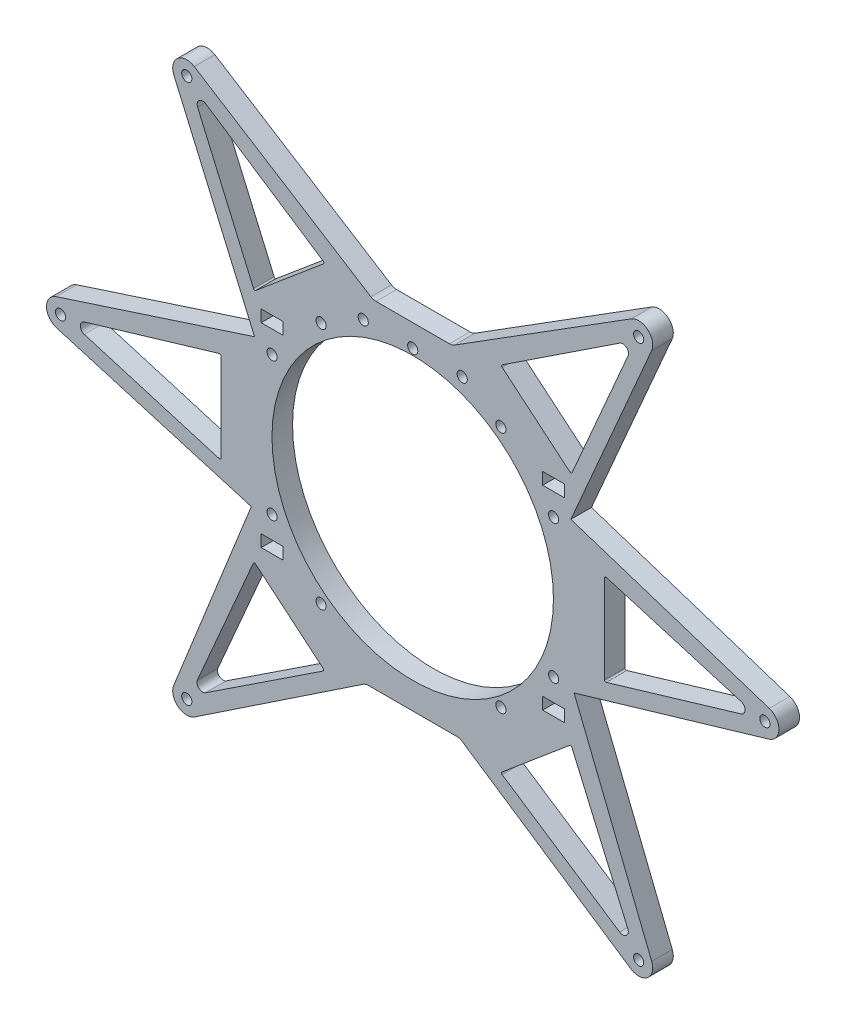
SolidWorks part; units mm, degrees
ref_plane "Front Plane" through (0, 0, 0) normal (0, 0, 1) x (1, 0, 0)
ref_plane "Top Plane" through (0, 0, 0) normal (0, 1, 0) x (1, 0, 0)
ref_plane "Right Plane" through (0, 0, 0) normal (1, 0, 0) x (0, 0, -1)
sketch "Sketch1" plane through (0, 0, 0) normal (0, 0, 1) x (1, 0, 0)
  line L0 (595.6845, 438.9915) -> (595.6626, 464.0842)
  line L1 (548.8362, 455.2938) -> (605.2132, 473.6179)
  line L2 (607.0986, 422.6607) -> (613.2986, 426.0607) construction
  line L3 (610.1986, 424.3607) -> (610.1986, 432.3607) construction
  line L4 (610.1986, 432.3607) -> (610.1986, 424.3607) construction
  line L5 (607.0986, 426.0607) -> (613.2986, 422.6607) construction
  line L6 (556.8144, 453.0549) -> (595.1528, 464.464)
  line L7 (556.8142, 450.0066) -> (595.1515, 438.5937)
  line L8 (548.9419, 447.6528) -> (604.2858, 431.3431)
  line L9 (624.7181, 401.7252) -> (605.4819, 417.8376)
  line L10 (607.0986, 426.0607) -> (607.0986, 422.6607)
  line L11 (607.0986, 426.0607) -> (613.2986, 426.0607)
  line L12 (613.2986, 426.0607) -> (613.2986, 422.6607)
  line L13 (588.9596, 380.9888) -> (604.8633, 417.6913)
  line L14 (588.0779, 531.5374) -> (638.2665, 499.9901)
  line L15 (591.2947, 379.0292) -> (624.6802, 401.0612)
  line L16 (607.0986, 422.6607) -> (613.2986, 422.6607)
  line L17 (709.0257, 523.9501) -> (675.6402, 501.9182)
  line L18 (639.7249, 499.5698) -> (660.5955, 499.5698)
  line L19 (589.0225, 522.0435) -> (604.9224, 485.3394)
  line L20 (637.6128, 403.9671) -> (641.8406, 403.9671)
  line L21 (690.1986, 470.2607) -> (690.1986, 433.8107) construction
  line L22 (693.2986, 481.4107) -> (687.0986, 478.0107) construction
  line L23 (690.1986, 479.7107) -> (690.1986, 471.7107) construction
  line L24 (582.2362, 376.3163) -> (604.2858, 431.3431)
  line L25 (675.6023, 501.2542) -> (694.8386, 485.1417)
  line L26 (582.2787, 526.5609) -> (605.2132, 473.6179)
  line L27 (690.1986, 471.7107) -> (690.1986, 479.7107) construction
  line L28 (712.2426, 531.5374) -> (662.0539, 499.9901)
  line L29 (650.0692, 451.5983) -> (-31455.4559, 38782.203) construction
  line L30 (605.5697, 485.1868) -> (624.7777, 501.3329)
  line L31 (591.3577, 524.0028) -> (624.741, 501.9675)
  line L32 (625.1052, 486.4638) -> (676.2052, 486.4388) construction
  line L33 (676.2052, 486.4388) -> (676.2052, 417.3888) construction
  line L34 (650.5503, 451.9554) -> (-31454.9748, -37878.6493) construction
  line L35 (588.1707, 371.5021) -> (636.1508, 403.5468)
  line L36 (711.3608, 521.9906) -> (695.4572, 485.2881)
  line L37 (704.6359, 463.9879) -> (704.6579, 438.8952)
  line L38 (743.506, 449.9245) -> (705.1676, 438.5154)
  line L39 (-349.7202, 451.4897) -> (49650.2798, 451.4897) construction
  line L40 (751.4842, 455.2938) -> (695.1073, 473.6179)
  line L41 (743.5062, 452.9728) -> (705.1689, 464.3857)
  line L42 (694.7507, 417.7926) -> (675.5427, 401.6465)
  line L43 (718.0417, 526.5609) -> (695.1073, 473.6179)
  line L44 (708.9627, 378.9765) -> (675.5794, 401.0119)
  line L45 (711.2979, 380.9358) -> (695.398, 417.64)
  line L48 (751.3785, 447.6528) -> (696.0347, 431.3431)
  line L51 (718.0843, 376.3163) -> (696.0347, 431.3431)
  line L54 (712.1497, 371.5021) -> (664.1696, 403.5468)
  line L57 (650.1602, 493.2598) -> (664.2332, 493.2598) construction
  line L58 (650.1602, 493.2598) -> (636.0872, 493.2598) construction
  line L64 (693.2986, 478.0107) -> (687.0986, 481.4107) construction
  line L65 (693.2986, 426.0607) -> (687.0986, 422.6607) construction
  line L66 (690.1986, 432.3607) -> (690.1986, 424.3607) construction
  line L70 (690.1986, 424.3607) -> (690.1986, 432.3607) construction
  line L72 (662.7113, 403.9671) -> (641.8406, 403.9671)
  line L111 (650.1602, -499.8735) -> (650.1602, 49500.1265) construction
  line L113 (693.2986, 422.6607) -> (687.0986, 426.0607) construction
  line L115 (693.2986, 478.0107) -> (693.2986, 481.4107)
  line L116 (693.2986, 478.0107) -> (687.0986, 478.0107)
  line L117 (687.0986, 478.0107) -> (687.0986, 481.4107)
  line L118 (693.2986, 481.4107) -> (687.0986, 481.4107)
  line L119 (693.2986, 422.6607) -> (687.0986, 422.6607)
  line L120 (687.0986, 426.0607) -> (687.0986, 422.6607)
  line L121 (693.2986, 426.0607) -> (687.0986, 426.0607)
  line L122 (693.2986, 426.0607) -> (693.2986, 422.6607)
  line L124 (617.7956, 472.7736) -> (611.5957, 472.7736) [skipped]
  line L125 (617.7956, 476.1737) -> (617.7956, 472.7736) [skipped]
  line L126 (611.5957, 476.1737) -> (617.7956, 476.1737) [skipped]
  line L127 (611.5957, 472.7736) -> (611.5957, 476.1737) [skipped]
  line L128 (611.5957, 429.3927) -> (611.5957, 425.9927) [skipped]
  line L129 (617.7956, 429.3927) -> (611.5957, 429.3927) [skipped]
  line L130 (617.7956, 425.9927) -> (617.7956, 429.3927) [skipped]
  line L131 (611.5957, 425.9927) -> (617.7956, 425.9927) [skipped]
  line L132 (690.8405, 474.1442) -> (690.8405, 477.5442) [skipped]
  line L133 (684.6405, 474.1442) -> (690.8405, 474.1442) [skipped]
  line L134 (684.6405, 477.5442) -> (684.6405, 474.1442) [skipped]
  line L135 (690.8405, 477.5442) -> (684.6405, 477.5442) [skipped]
  line L136 (690.8405, 427.3632) -> (684.6405, 427.3632) [skipped]
  line L137 (684.6405, 427.3632) -> (684.6405, 430.7633) [skipped]
  line L138 (684.6405, 430.7633) -> (690.8405, 430.7633) [skipped]
  line L139 (690.8405, 430.7633) -> (690.8405, 427.3632) [skipped]
  line L143 (675.2153, 417.4138) -> (624.1153, 417.3888) construction
  line L149 (563.3561, 455.4189) -> (600.7262, 466.9846) [skipped]
  line L151 (563.3561, 448.0054) -> (600.7262, 436.4397) [skipped]
  line L153 (604.6131, 439.3056) -> (604.6131, 464.1187) [skipped]
  line L154 (739.08, 455.5315) -> (701.71, 467.0972) [skipped]
  line L155 (739.08, 448.118) -> (701.71, 436.5523) [skipped]
  line L156 (697.823, 464.2313) -> (697.823, 439.4182) [skipped]
  line L157 (607.0986, 481.4107) -> (613.2986, 481.4107)
  line L158 (613.2986, 478.0107) -> (613.2986, 481.4107)
  line L159 (607.0986, 478.0107) -> (613.2986, 481.4107) construction
  line L160 (610.1986, 471.7107) -> (610.1986, 479.7107) construction
  line L161 (610.1986, 479.7107) -> (610.1986, 471.7107) construction
  line L162 (607.0986, 481.4107) -> (613.2986, 478.0107) construction
  line L163 (607.0986, 478.0107) -> (613.2986, 478.0107)
  line L164 (607.0986, 478.0107) -> (607.0986, 481.4107)
  line L165 (610.1986, 470.2607) -> (610.1986, 433.6599) construction
  line L167 (582.8453, 522.4022) -> (593.6044, 531.4302) construction
  line L168 (583.7109, 532.2958) -> (592.7389, 521.5367) construction
  line L169 (624.1153, 486.4388) -> (624.1153, 417.3888) construction
  line L171 (675.2153, 486.4638) -> (624.1153, 486.4388) construction
  line L173 (583.6746, 550.3006) -> (584.9049, 548.8344) [skipped]
  line L175 (585.5941, 545.7572) -> (585.4387, 544.8758) [skipped]
  line L177 (576.519, 551.5332) -> (581.3031, 551.5332) [skipped]
  line L179 (585.3957, 559.7761) -> (574.9031, 550.9717) [skipped]
  line L181 (601.5986, 538.696) -> (576.7757, 538.696) [skipped]
  line L183 (584.3076, 550.5785) -> (585.8424, 548.7494) [skipped]
  line L185 (584.5241, 558.2576) -> (583.5948, 552.9875) [skipped]
  line L187 (589.9222, 383.8286) -> (592.5341, 381.637) [skipped]
  line L189 (579.4748, 367.5157) -> (577.8777, 368.8559) [skipped]
  line L191 (576.7421, 370.8231) -> (575.4793, 377.9843) [skipped]
  line L193 (576.2058, 380.6953) -> (577.3653, 382.0772) [skipped]
  line L195 (579.909, 383.2633) -> (580.8883, 383.2633) [skipped]
  line L197 (593.2925, 371.9562) -> (593.1226, 372.9191) [skipped]
  line L199 (595.4215, 381.4396) -> (619.5023, 396.5929) [skipped]
  line L201 (591.4517, 367.9234) -> (592.5577, 369.2416) [skipped]
  line L203 (581.6093, 366.7384) -> (588.9059, 366.7384) [skipped]
  line L205 (619.773, 400.5538) -> (603.8217, 413.9386) [skipped]
  line L207 (589.2265, 386.6378) -> (599.9679, 412.9842) [skipped]
  line L209 (589.8641, 370.3626) -> (579.105, 379.3905) construction
  line L211 (588.9985, 380.2561) -> (579.9706, 369.497) construction
  line L213 (594.6523, 376.2433) -> (637.861, 403.1093) [skipped]
  line L215 (583.9631, 385.3302) -> (601.6058, 428.6038) [skipped]
  line L217 (561.2431, 453.4732) -> (561.2431, 450.0637) [skipped]
  line L219 (542.109, 451.6827) -> (542.109, 452.594) [skipped]
  line L221 (542.8859, 454.7284) -> (547.5376, 460.2722) [skipped]
  line L223 (550.0813, 461.4583) -> (551.8779, 461.4583) [skipped]
  line L225 (554.4215, 460.2722) -> (555.0557, 459.5164) [skipped]
  line L227 (554.3399, 444.0403) -> (554.9817, 444.8052) [skipped]
  line L229 (550.0512, 442.8542) -> (551.7962, 442.8542) [skipped]
  line L231 (542.8859, 449.5483) -> (547.5075, 444.0403) [skipped]
  line L233 (550.9061, 444.7459) -> (550.9061, 458.791) construction
  line L235 (557.8991, 451.5018) -> (543.8541, 451.5018) construction
  line L237 (558.5415, 445.832) -> (599.7486, 432.5865) [skipped]
  line L239 (558.6155, 458.4895) -> (602.6275, 472.6364) [skipped]
  line L240 (706.5283, 383.3485) -> (709.4303, 385.7836) [skipped]
  line L241 (717.0405, 343.7608) -> (727.5331, 352.5652) [skipped]
  line L242 (725.9172, 352.0037) -> (721.1331, 352.0037) [skipped]
  line L243 (718.7616, 353.2363) -> (717.5313, 354.7025) [skipped]
  line L244 (716.842, 357.7797) -> (716.9974, 358.6611) [skipped]
  line L245 (722.7253, 366.7402) -> (664.201, 403.5271) [skipped]
  line L246 (741.1931, 450.0637) -> (741.1931, 453.4732) [skipped]
  line L247 (700.8376, 364.8409) -> (725.6604, 364.8409) [skipped]
  line L248 (713.4137, 381.4934) -> (697.5138, 418.1975) [skipped]
  line L249 (718.1285, 352.9584) -> (716.5938, 354.7875) [skipped]
  line L250 (717.9121, 345.2793) -> (718.8413, 350.5494) [skipped]
  line L251 (723.9579, 368.2028) -> (698.1406, 427.8006) [skipped]
  line L252 (696.8664, 418.3501) -> (677.6584, 402.204) [skipped]
  line L253 (711.0784, 379.5341) -> (677.6952, 401.5694) [skipped]
  line L254 (760.3271, 451.8543) -> (760.3271, 450.9429) [skipped]
  line L255 (759.5503, 448.8085) -> (754.8986, 443.2647) [skipped]
  line L256 (752.3549, 442.0786) -> (750.5583, 442.0786) [skipped]
  line L257 (748.0146, 443.2647) -> (747.3804, 444.0205) [skipped]
  line L258 (743.8206, 445.0474) -> (699.8086, 430.9005) [skipped]
  line L259 (748.0962, 459.4966) -> (747.4545, 458.7317) [skipped]
  line L260 (752.3849, 460.6827) -> (750.6399, 460.6827) [skipped]
  line L261 (759.5503, 453.9886) -> (754.9286, 459.4966) [skipped]
  line L262 (743.8947, 457.7049) -> (702.6875, 470.9504) [skipped]
  line L263 (712.5139, 519.7083) -> (709.902, 521.8999) [skipped]
  line L264 (722.9613, 536.0212) -> (724.5585, 534.681) [skipped]
  line L265 (725.6941, 532.7138) -> (726.9568, 525.5526) [skipped]
  line L266 (726.2304, 522.8416) -> (725.0708, 521.4597) [skipped]
  line L267 (722.5271, 520.2736) -> (721.5478, 520.2736) [skipped]
  line L268 (718.473, 518.2067) -> (700.8303, 474.9331) [skipped]
  line L269 (709.1436, 531.5807) -> (709.3136, 530.6178) [skipped]
  line L270 (707.0147, 522.0973) -> (682.9338, 506.944) [skipped]
  line L271 (710.9845, 535.6135) -> (709.8784, 534.2953) [skipped]
  line L272 (720.8268, 536.7985) -> (713.5302, 536.7985) [skipped]
  line L273 (707.7839, 527.2936) -> (664.5752, 500.4276) [skipped]
  line L274 (682.6631, 502.9831) -> (698.6145, 489.5983) [skipped]
  line L275 (713.2097, 516.8991) -> (702.4682, 490.5527) [skipped]
  line L276 (719.5908, 381.1347) -> (708.8317, 372.1067) construction
  line L277 (718.7252, 371.2411) -> (709.6973, 382.0002) construction
  line L278 (751.5301, 458.791) -> (751.5301, 444.7459) construction
  line L279 (744.537, 452.0351) -> (758.582, 452.0351) construction
  line L280 (712.572, 533.1743) -> (723.3312, 524.1464) construction
  line L281 (713.4376, 523.2808) -> (722.4656, 534.0399) construction
  line L282 (664.8233, 499.5698) -> (660.5955, 499.5698) [skipped]
  line L283 (585.9139, 528.2488) -> (591.8687, 521.0811) construction
  line L284 (595.6314, 439.0288) -> (595.5403, 464.1213) [skipped]
  line L285 (704.689, 439.0288) -> (704.7802, 464.1213) [skipped]
  line L286 (743.5977, 452.9849) -> (705.291, 464.4997) [skipped]
  line L287 (743.5895, 449.9366) -> (705.2209, 438.6295) [skipped]
  line L288 (744.7442, 451.4259) -> (744.734, 447.7303) [skipped]
  line L289 (549.9748, 451.5254) -> (559.2934, 451.5054) construction
  line L290 (585.8591, 374.7763) -> (591.8446, 381.9184) construction
  line L291 (595.9078, 520.1884) -> (593.0059, 517.7533) [skipped]
  line L292 (595.7978, 519.8758) -> (593.4586, 517.9131) [skipped]
  line L293 (592.3268, 385.9998) -> (594.6767, 384.0498) [skipped]
  line L294 (556.7227, 452.9849) -> (595.0295, 464.4997) [skipped]
  line L295 (556.7309, 449.9366) -> (595.0995, 438.6295) [skipped]
  line L296 (624.7051, 401.8259) -> (605.3803, 417.8319) [skipped]
  line L297 (589.0616, 380.8924) -> (604.7625, 417.6821) [skipped]
  line L298 (591.4074, 378.9458) -> (624.6709, 401.1616) [skipped]
  line L299 (562.7361, 453.75) -> (562.7444, 450.6964) [skipped]
  line L300 (675.6153, 401.8259) -> (694.9402, 417.8319) [skipped]
  line L301 (711.2588, 380.8924) -> (695.5579, 417.6821) [skipped]
  line L302 (710.7963, 379.0134) -> (707.9522, 376.6535) [skipped]
  line L303 (708.913, 378.9458) -> (675.6496, 401.1616) [skipped]
  line L304 (708.9627, 524.0028) -> (675.5794, 501.9675) [skipped]
  line L305 (694.7507, 485.1868) -> (675.5427, 501.3329) [skipped]
  line L306 (711.2979, 522.0435) -> (695.398, 485.3394) [skipped]
  line L307 (710.8942, 523.8843) -> (713.7253, 521.5087) [skipped]
  arc A0 (588.0779, 531.5374) -> (582.2787, 526.5609) centre (585.9492, 528.1509) ccw
  arc A1 (548.8362, 455.2938) -> (548.9419, 447.6528) centre (550.0726, 451.4897) ccw
  circle A2 centre (585.9492, 528.1509) radius 1.45
  circle A3 centre (550.0726, 451.4897) radius 1.45
  arc A4 (595.1528, 464.464) -> (595.6626, 464.0842) centre (595.2659, 464.0838) cw
  arc A5 (556.8142, 450.0066) -> (556.8144, 453.0549) centre (557.268, 451.5307) cw
  arc A6 (595.6845, 438.9915) -> (595.1515, 438.5937) centre (595.2698, 438.9911) cw
  circle A7 centre (675.2153, 486.4638) radius 1.4499
  arc A8 (605.5697, 485.1868) -> (604.9224, 485.3394) centre (605.3029, 485.5042) cw
  arc A9 (589.0225, 522.0435) -> (591.3577, 524.0028) centre (590.4817, 522.6757) cw
  arc A10 (604.8633, 417.6913) -> (605.4819, 417.8376) centre (605.2272, 417.5336) cw
  arc A11 (591.2947, 379.0292) -> (588.9596, 380.9888) centre (590.4188, 380.3565) cw
  arc A12 (624.7181, 401.7252) -> (624.6802, 401.0612) centre (624.4518, 401.4073) cw
  arc A13 (675.6023, 501.2542) -> (675.6402, 501.9182) centre (675.8686, 501.5721) cw
  arc A14 (582.2362, 376.3163) -> (588.1707, 371.5021) centre (585.9492, 374.8285) ccw
  arc A15 (624.741, 501.9675) -> (624.7777, 501.3329) centre (624.5225, 501.6365) cw
  circle A16 centre (650.1602, 451.4897) radius 40
  circle A17 centre (585.9492, 374.8285) radius 1.45
  arc A18 (695.4572, 485.2881) -> (694.8386, 485.1417) centre (695.0932, 485.4458) cw
  arc A19 (709.0257, 523.9501) -> (711.3608, 521.9906) centre (709.9016, 522.6229) cw
  arc A20 (705.1676, 438.5154) -> (704.6579, 438.8952) centre (705.0545, 438.8956) cw
  arc A21 (743.5062, 452.9728) -> (743.506, 449.9245) centre (743.0524, 451.4486) cw
  circle A22 centre (650.1602, 493.2598) radius 1.45
  arc A23 (704.6359, 463.9879) -> (705.1689, 464.3857) centre (705.0506, 463.9882) cw
  arc A24 (675.5794, 401.0119) -> (675.5427, 401.6465) centre (675.7979, 401.3429) cw
  arc A25 (711.2979, 380.9358) -> (708.9627, 378.9765) centre (709.8387, 380.3037) cw
  circle A26 centre (714.3713, 528.1509) radius 1.45
  arc A27 (712.2426, 531.5374) -> (718.0417, 526.5609) centre (714.3713, 528.1509) cw
  arc A28 (660.5955, 499.5698) -> (662.0539, 499.9901) centre (660.5955, 502.3102) ccw
  arc A29 (694.7507, 417.7926) -> (695.398, 417.64) centre (695.0175, 417.4751) cw
  circle A32 centre (610.1986, 432.3607) radius 1.45
  circle A33 centre (690.1986, 471.7107) radius 1.45
  circle A36 centre (750.2478, 451.4897) radius 1.45
  arc A37 (751.4842, 455.2938) -> (751.3785, 447.6528) centre (750.2478, 451.4897) cw
  circle A42 centre (714.3713, 374.8285) radius 1.45
  arc A43 (718.0843, 376.3163) -> (712.1497, 371.5021) centre (714.3713, 374.8285) cw
  circle A44 centre (636.0872, 493.2598) radius 1.45
  circle A45 centre (664.2332, 493.2598) radius 1.45
  circle A87 centre (690.1986, 432.3607) radius 1.45
  arc A114 (638.2665, 499.9901) -> (639.7249, 499.5698) centre (639.7249, 502.3102) ccw
  arc A116 (636.1508, 403.5468) -> (637.6128, 403.9671) centre (637.6128, 401.2139) cw
  arc A117 (664.1696, 403.5468) -> (662.7113, 403.9671) centre (662.7113, 401.2267) ccw
  circle A119 centre (624.1153, 417.3888) radius 1.4499
  circle A120 centre (613.6609, 439.3632) radius 1.4499 [skipped]
  circle A121 centre (687.2375, 434.0512) radius 1.45 [skipped]
  circle A122 centre (688.7752, 464.1737) radius 1.4499 [skipped]
  arc A124 (599.7067, 467.3082) -> (603.5937, 464.4423) centre (600.5937, 464.4423) cw [skipped]
  arc A126 (603.5937, 439.6292) -> (599.7067, 436.7633) centre (600.5937, 439.6292) cw [skipped]
  arc A127 (698.8425, 463.9077) -> (702.7295, 466.7736) centre (701.8425, 463.9077) cw [skipped]
  arc A128 (702.7295, 436.2287) -> (698.8425, 439.0946) centre (701.8425, 439.0946) cw [skipped]
  circle A129 centre (610.1986, 471.7107) radius 1.45
  circle A130 centre (615.1986, 469.4857) radius 1.45 [skipped]
  circle A131 centre (624.1153, 486.4388) radius 1.4499
  circle A132 centre (675.2153, 417.4138) radius 1.4499
  circle A134 centre (581.8553, 522.8608) radius 0.8749 [skipped]
  circle A136 centre (582.7209, 532.7543) radius 0.8749 [skipped]
  circle A138 centre (592.6145, 531.8887) radius 0.8749 [skipped]
  circle A140 centre (591.7489, 521.9952) radius 0.8749 [skipped]
  arc A142 (579.0007, 537.4897) -> (584.4487, 545.3343) centre (581.7247, 541.412) cw [skipped]
  arc A144 (584.6041, 546.2157) -> (583.9149, 549.293) centre (581.4079, 547.1156) ccw [skipped]
  arc A146 (582.6846, 550.7592) -> (580.3131, 551.9917) centre (580.097, 548.6782) ccw [skipped]
  arc A148 (578.9176, 537.0156) -> (575.7857, 539.1545) centre (575.8144, 535.8341) ccw [skipped]
  arc A150 (575.529, 551.9917) -> (573.9131, 551.4303) centre (575.7741, 548.6802) ccw [skipped]
  arc A152 (600.6086, 539.1545) -> (584.8524, 549.208) centre (590.5191, 540.7154) cw [skipped]
  arc A154 (583.3176, 551.037) -> (582.6048, 553.446) centre (585.9087, 553.1136) cw [skipped]
  arc A156 (583.5341, 558.7161) -> (584.4057, 560.2346) centre (586.7478, 557.8808) cw [skipped]
  circle A158 centre (578.115, 379.8491) radius 0.8749 [skipped]
  circle A160 centre (578.9806, 369.9555) radius 0.8749 [skipped]
  circle A162 centre (583.4651, 375.0684) radius 1.45 [skipped]
  circle A164 centre (588.8741, 370.8211) radius 0.8749 [skipped]
  circle A166 centre (588.0085, 380.7146) radius 0.8749 [skipped]
  arc A168 (593.6623, 376.7019) -> (592.1326, 373.3776) centre (595.3883, 373.8935) ccw [skipped]
  arc A170 (618.783, 401.0124) -> (618.5123, 397.0514) centre (617.204, 399.1306) cw [skipped]
  arc A172 (594.4315, 381.8982) -> (591.5441, 382.0955) centre (593.1231, 383.9773) cw [skipped]
  arc A174 (588.9322, 384.2872) -> (588.2365, 387.0964) centre (590.5113, 386.169) cw [skipped]
  arc A176 (582.9731, 385.7888) -> (579.8983, 383.7219) centre (579.8983, 387.0424) cw [skipped]
  arc A178 (578.919, 383.7219) -> (576.3753, 382.5357) centre (578.919, 380.4013) ccw [skipped]
  arc A180 (575.2158, 381.1539) -> (574.4894, 378.4428) centre (577.7595, 379.0194) ccw [skipped]
  arc A182 (575.7521, 371.2816) -> (576.8877, 369.3144) centre (579.0222, 371.8581) ccw [skipped]
  arc A184 (598.9779, 413.4427) -> (602.8317, 414.3971) centre (601.2527, 412.5153) cw [skipped]
  arc A186 (592.3025, 372.4147) -> (591.5677, 369.7002) centre (589.0276, 371.8445) cw [skipped]
  arc A188 (590.4617, 368.382) -> (587.9159, 367.197) centre (587.9185, 370.5184) cw [skipped]
  arc A190 (580.6193, 367.197) -> (578.4848, 367.9743) centre (580.6199, 370.5177) cw [skipped]
  circle A192 centre (549.9161, 459.2495) radius 0.8749 [skipped]
  circle A194 centre (542.8641, 451.9603) radius 0.8749 [skipped]
  circle A196 centre (549.8866, 451.9603) radius 1.45 [skipped]
  circle A198 centre (549.9161, 445.2045) radius 0.8749 [skipped]
  circle A200 centre (556.9091, 451.9603) radius 0.8749 [skipped]
  arc A202 (557.5515, 446.2905) -> (553.9917, 445.2637) centre (556.5353, 443.1293) ccw [skipped]
  arc A204 (561.9579, 448.1835) -> (560.2531, 450.5222) centre (562.7096, 450.5222) cw [skipped]
  arc A206 (560.2531, 453.9318) -> (561.9579, 456.2705) centre (562.7096, 453.9318) cw [skipped]
  arc A208 (557.6255, 458.9481) -> (554.0657, 459.9749) centre (556.6094, 462.1093) cw [skipped]
  arc A210 (553.4315, 460.7307) -> (550.8879, 461.9168) centre (550.8879, 458.5963) ccw [skipped]
  arc A212 (549.0913, 461.9168) -> (546.5476, 460.7307) centre (549.0913, 458.5963) ccw [skipped]
  arc A214 (541.8959, 455.187) -> (541.119, 453.0526) centre (544.4395, 453.0526) ccw [skipped]
  arc A216 (553.3499, 444.4989) -> (550.8062, 443.3128) centre (550.8062, 446.6333) cw [skipped]
  arc A218 (549.0612, 443.3128) -> (546.5176, 444.4989) centre (549.0612, 446.6333) cw [skipped]
  arc A220 (541.8959, 450.0068) -> (541.119, 452.1412) centre (544.4395, 452.1412) cw [skipped]
  arc A221 (600.6158, 429.0624) -> (598.7586, 433.0451) centre (597.842, 430.1933) ccw [skipped]
  arc A222 (601.6375, 473.095) -> (603.4379, 476.8726) centre (600.6019, 475.9064) ccw [skipped]
  circle A223 centre (709.8217, 371.6482) radius 0.8749 [skipped]
  circle A224 centre (719.7152, 370.7826) radius 0.8749 [skipped]
  circle A225 centre (716.487, 375.386) radius 1.45 [skipped]
  circle A226 centre (720.5808, 380.6761) radius 0.8749 [skipped]
  circle A227 centre (710.6873, 381.5417) radius 0.8749 [skipped]
  arc A228 (723.5186, 366.5213) -> (726.6504, 364.3824) centre (726.6218, 367.7028) ccw [skipped]
  arc A229 (696.8664, 418.3501) -> (697.5138, 418.1975) centre (697.1333, 418.0327) cw [skipped]
  arc A230 (710.5437, 387.4921) -> (710.0915, 385.6105) centre (709.0457, 386.8569) cw [skipped]
  arc A231 (707.1896, 383.1755) -> (705.2581, 383.057) centre (706.1437, 384.4219) cw [skipped]
  arc A232 (723.4355, 366.0472) -> (717.9874, 358.2026) centre (720.7115, 362.1249) cw [skipped]
  arc A233 (717.832, 357.3212) -> (718.5213, 354.2439) centre (721.0283, 356.4213) ccw [skipped]
  arc A234 (719.7516, 352.7777) -> (722.1231, 351.5452) centre (722.3392, 354.8587) ccw [skipped]
  arc A235 (726.9072, 351.5452) -> (728.5231, 352.1066) centre (726.6621, 354.8567) ccw [skipped]
  arc A236 (677.6952, 401.5694) -> (677.6584, 402.204) centre (677.9136, 401.9004) cw [skipped]
  circle A237 centre (752.5201, 444.2874) radius 0.8749 [skipped]
  circle A238 centre (759.572, 451.5766) radius 0.8749 [skipped]
  arc A239 (701.8276, 364.3824) -> (717.5838, 354.329) centre (711.9171, 362.8215) cw [skipped]
  circle A240 centre (752.5495, 451.5766) radius 1.45 [skipped]
  circle A241 centre (752.5201, 458.3324) radius 0.8749 [skipped]
  circle A242 centre (745.527, 451.5766) radius 0.8749 [skipped]
  arc A243 (744.8847, 457.2464) -> (748.4445, 458.2732) centre (745.9008, 460.4076) ccw [skipped]
  arc A244 (740.4783, 455.3534) -> (742.1831, 453.0147) centre (739.7265, 453.0147) cw [skipped]
  arc A245 (742.1831, 449.6051) -> (740.4783, 447.2664) centre (739.7265, 449.6051) cw [skipped]
  arc A246 (744.8106, 444.5888) -> (748.3704, 443.562) centre (745.8267, 441.4276) cw [skipped]
  arc A247 (749.0046, 442.8062) -> (751.5483, 441.6201) centre (751.5483, 444.9406) ccw [skipped]
  arc A248 (753.3449, 441.6201) -> (755.8886, 442.8062) centre (753.3449, 444.9406) ccw [skipped]
  arc A249 (719.1185, 352.4999) -> (719.8313, 350.0909) centre (716.5275, 350.4233) cw [skipped]
  arc A250 (760.5403, 448.3499) -> (761.3171, 450.4843) centre (757.9966, 450.4843) ccw [skipped]
  arc A251 (749.0862, 459.038) -> (751.6299, 460.2241) centre (751.6299, 456.9036) cw [skipped]
  arc A252 (753.3749, 460.2241) -> (755.9186, 459.038) centre (753.3749, 456.9036) cw [skipped]
  arc A253 (760.5403, 453.5301) -> (761.3171, 451.3957) centre (757.9966, 451.3957) cw [skipped]
  circle A254 centre (724.3212, 523.6878) radius 0.8749 [skipped]
  circle A255 centre (723.4556, 533.5814) radius 0.8749 [skipped]
  circle A256 centre (718.9711, 528.4685) radius 1.45 [skipped]
  circle A257 centre (713.562, 532.7158) radius 0.8749 [skipped]
  circle A258 centre (714.4276, 522.8223) radius 0.8749 [skipped]
  arc A259 (708.7739, 526.835) -> (710.3036, 530.1593) centre (707.0479, 529.6434) ccw [skipped]
  arc A260 (683.6531, 502.5245) -> (683.9238, 506.4855) centre (685.2321, 504.4063) cw [skipped]
  arc A261 (708.0047, 521.6387) -> (710.892, 521.4414) centre (709.313, 519.5596) cw [skipped]
  arc A262 (713.5039, 519.2497) -> (714.1997, 516.4405) centre (711.9249, 517.3679) cw [skipped]
  arc A263 (719.463, 517.7481) -> (722.5378, 519.815) centre (722.5378, 516.4945) cw [skipped]
  arc A264 (723.5171, 519.815) -> (726.0608, 521.0012) centre (723.5172, 523.1356) ccw [skipped]
  arc A265 (718.9021, 344.8208) -> (718.0305, 343.3023) centre (715.6883, 345.6561) cw [skipped]
  arc A266 (727.2203, 522.383) -> (727.9468, 525.0941) centre (724.6767, 524.5175) ccw [skipped]
  arc A267 (726.6841, 532.2553) -> (725.5485, 534.2225) centre (723.4139, 531.6788) ccw [skipped]
  arc A268 (703.4582, 490.0942) -> (699.6045, 489.1398) centre (701.1835, 491.0216) cw [skipped]
  arc A269 (710.1336, 531.1222) -> (710.8684, 533.8367) centre (713.4085, 531.6924) cw [skipped]
  arc A270 (711.9745, 535.1549) -> (714.5202, 536.3399) centre (714.5176, 533.0185) cw [skipped]
  arc A271 (721.8168, 536.3399) -> (723.9513, 535.5626) centre (721.8163, 533.0192) cw [skipped]
  arc A272 (701.8203, 474.4745) -> (703.6775, 470.4918) centre (704.5942, 473.3436) ccw [skipped]
  arc A273 (700.7986, 430.4419) -> (698.9982, 426.6643) centre (701.8342, 427.6305) ccw [skipped]
  arc A274 (666.2854, 499.9901) -> (664.8233, 499.5698) centre (664.8233, 502.323) cw [skipped]
  circle A275 centre (637.1344, 408.7932) radius 1.45 [skipped]
  arc A276 (595.0295, 464.4997) -> (595.5403, 464.1213) centre (595.1436, 464.1198) cw [skipped]
  arc A277 (595.6314, 439.0288) -> (595.0995, 438.6295) centre (595.2168, 439.0273) cw [skipped]
  circle A278 centre (608.9442, 433.9492) radius 1.45 [skipped]
  arc A279 (705.291, 464.4997) -> (704.7802, 464.1213) centre (705.1768, 464.1198) ccw [skipped]
  arc A280 (704.689, 439.0288) -> (705.2209, 438.6295) centre (705.1037, 439.0273) ccw [skipped]
  arc A281 (744.7442, 451.4259) -> (743.5977, 452.9849) centre (743.1171, 451.4304) ccw [skipped]
  arc A282 (743.5895, 449.9366) -> (744.734, 447.7303) centre (745.094, 449.317) ccw [skipped]
  arc A283 (591.8925, 516.0448) -> (592.3446, 517.9264) centre (593.3905, 516.68) cw [skipped]
  arc A284 (589.0225, 522.0435) -> (593.4586, 517.9131) centre (595.9628, 525.05) cw [skipped]
  arc A285 (595.2466, 520.3614) -> (597.178, 520.4799) centre (596.2924, 519.115) cw [skipped]
  arc A286 (595.7978, 519.8758) -> (591.3577, 524.0028) centre (593.5778, 521.9393) cw [skipped]
  arc A287 (562.7361, 453.75) -> (556.7227, 452.9849) centre (559.7294, 453.3674) cw [skipped]
  arc A288 (556.7309, 449.9366) -> (562.7444, 450.6964) centre (558.869, 457.1916) cw [skipped]
  arc A289 (591.4074, 378.9458) -> (594.6767, 384.0498) centre (587.2067, 385.2355) cw [skipped]
  arc A290 (592.3268, 385.9998) -> (589.0616, 380.8924) centre (590.6942, 383.4461) cw [skipped]
  arc A291 (604.7625, 417.6821) -> (605.3803, 417.8319) centre (605.1273, 417.5265) cw [skipped]
  arc A292 (624.7051, 401.8259) -> (624.6709, 401.1616) centre (624.4406, 401.5065) cw [skipped]
  arc A293 (695.5579, 417.6821) -> (694.9402, 417.8319) centre (695.1932, 417.5265) ccw [skipped]
  arc A294 (710.7963, 379.0134) -> (711.2588, 380.8924) centre (709.7573, 380.2656) ccw [skipped]
  arc A295 (708.913, 378.9458) -> (707.9522, 376.6535) centre (709.4011, 377.3937) ccw [skipped]
  arc A296 (675.6153, 401.8259) -> (675.6496, 401.1616) centre (675.8799, 401.5065) ccw [skipped]
  arc A297 (675.5794, 501.9675) -> (675.5427, 501.3329) centre (675.7979, 501.6365) ccw [skipped]
  arc A298 (694.7507, 485.1868) -> (695.398, 485.3394) centre (695.0175, 485.5042) ccw [skipped]
  arc A299 (711.2979, 522.0435) -> (713.7253, 521.5087) centre (712.7376, 522.8017) ccw [skipped]
  arc A300 (710.8942, 523.8843) -> (708.9627, 524.0028) centre (709.8483, 522.6379) ccw [skipped]
  point P4 (604.5836, 472.839)
  point P5 (610.6788, 407.5004)
  point P6 (604.4805, 430.3607)
  point P7 (590.1096, 382.987)
  point P10 (592.2236, 451.9603)
  point P12 (560.2236, 451.9603)
  point P13 (615.0427, 409.8289)
  point P15 (595.5859, 451.575)
  point P16 (593.7956, 519.1439)
  point P18 (562.0153, 451.7438)
  point P21 (557.1601, 445.912)
  point P22 (691.7574, 496.0365)
  point P23 (586.2073, 519.1355)
  point P26 (605.1436, 484.8286)
  point P27 (593.4054, 384.161)
  point P31 (706.9167, 384.1702)
  point P32 (709.3005, 386.1481)
  point P33 (712.3266, 520.5499)
  point P34 (710.2125, 451.5766)
  point P37 (593.7956, 519.1439)
  point P38 (704.5328, 382.1922)
  point P39 (610.1986, 451.9603)
  point P40 (675.1867, 401.4708)
  point P41 (685.2778, 409.8289)
  point P43 (705.5495, 376.706)
  point P44 (637.2651, 404.097)
  point P45 (665.171, 403.5624)
  point P46 (743.1543, 445.9191)
  point P47 (650.1602, 451.4897)
  point P48 (685.1467, 493.2598)
  point P49 (742.2125, 451.5766)
  point P50 (687.2624, 410.2771)
  point P53 (695.1768, 484.8286)
  point P54 (615.1737, 493.2598)
  point P55 (708.8884, 517.1528)
  point P56 (706.5155, 519.1439)
  point P57 (714.1038, 519.1355)
  point P63 (625.1845, 501.6748)
  point P64 (708.6406, 384.393)
  point P66 (665.171, 499.4399)
  point P67 (704.1427, 521.135)
  point P78 (594.7726, 376.6969)
  point P93 (650.1602, 499.5698)
  point P143 (704.687, 438.4721)
  point P145 (738.2906, 448.6533)
  point P146 (704.7346, 451.575)
  point P147 (738.2991, 451.7509)
  point P148 (738.3077, 454.8484)
  point P168 (650.1986, 474.8257)
  point P186 (649.6653, 486.4513)
  point P195 (650.1986, 417.4013)
  point P345 (637.2651, 499.9745)
  point P357 (690.1986, 452.0357)
  point P359 (627.5086, 452.0357)
  point P360 (650.1986, 484.3109)
  point P366 (610.1986, 479.7107)
  point P387 (650.1986, 417.6202)
  dimension "D1" = 3
  dimension "D2" = 4
  dimension "D3" = 100
  dimension "D6" = 2
  dimension "D9" = 55.35
  dimension "D7" = 3
  dimension "D11" = 80
  dimension "D5" = 3
  dimension "D4" = 2
  dimension "D8" = 3
  dimension "D10" = 8
extrude "Boss-Extrude11" add sketch "Sketch1" along normal blind 5.85
